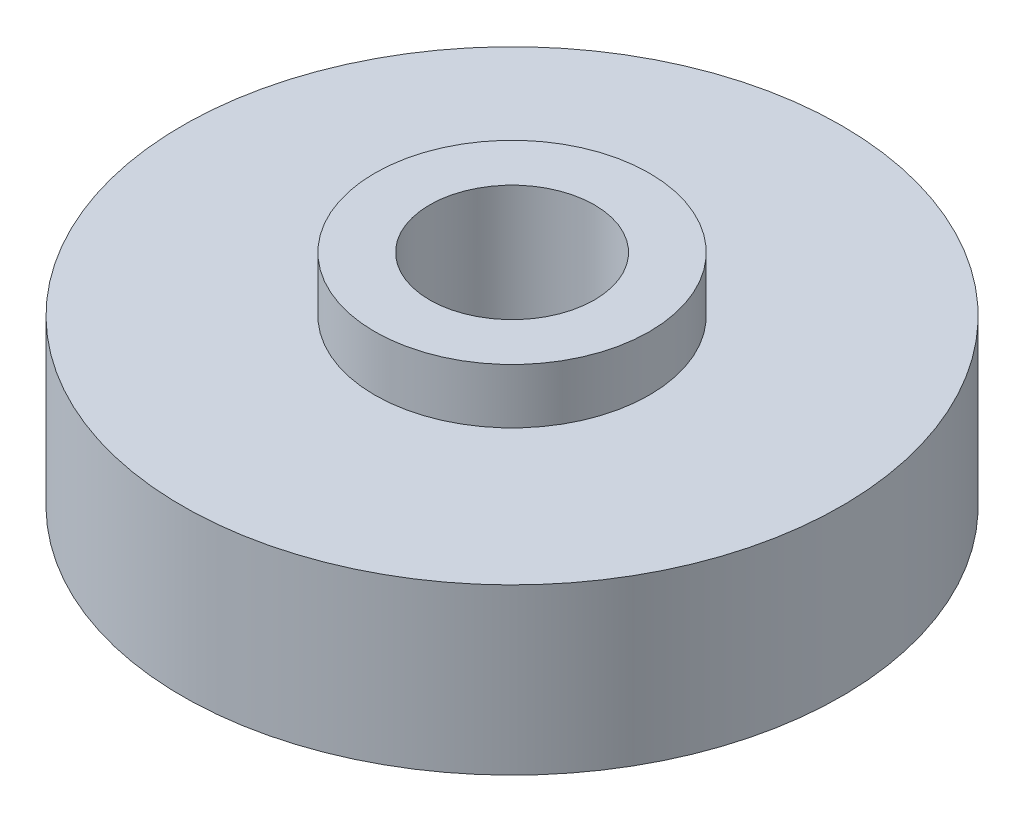
SolidWorks part; units mm, degrees
material "聚脂树脂"
ref_plane "前视基准面" through (0, 0, 0) normal (0, 0, 1) x (1, 0, 0)
ref_plane "上视基准面" through (0, 0, 0) normal (0, 1, 0) x (1, 0, 0)
ref_plane "右视基准面" through (0, 0, 0) normal (1, 0, 0) x (0, 0, -1)
other "Configuration Table"
sketch "草图1" plane through (0, 0, 0) normal (0, 1, 0) x (1, 0, 0)
  circle A0 centre (0, 0) radius 2.5
  circle A1 centre (0, 0) radius 1.5
  dimension "D1" = 3
  dimension "D2" = 5
extrude "凸台-拉伸1" add sketch "草图1" along normal blind 1
sketch "草图2" plane through (0, 0, 0) normal (0, -1, 0) x (1, 0, 0)
  circle A0 centre (0, 0) radius 1.5
  circle A1 centre (0, 0) radius 6
  dimension "D1" = 3
  dimension "D2" = 12
extrude "凸台-拉伸2" add sketch "草图2" along normal blind 3
